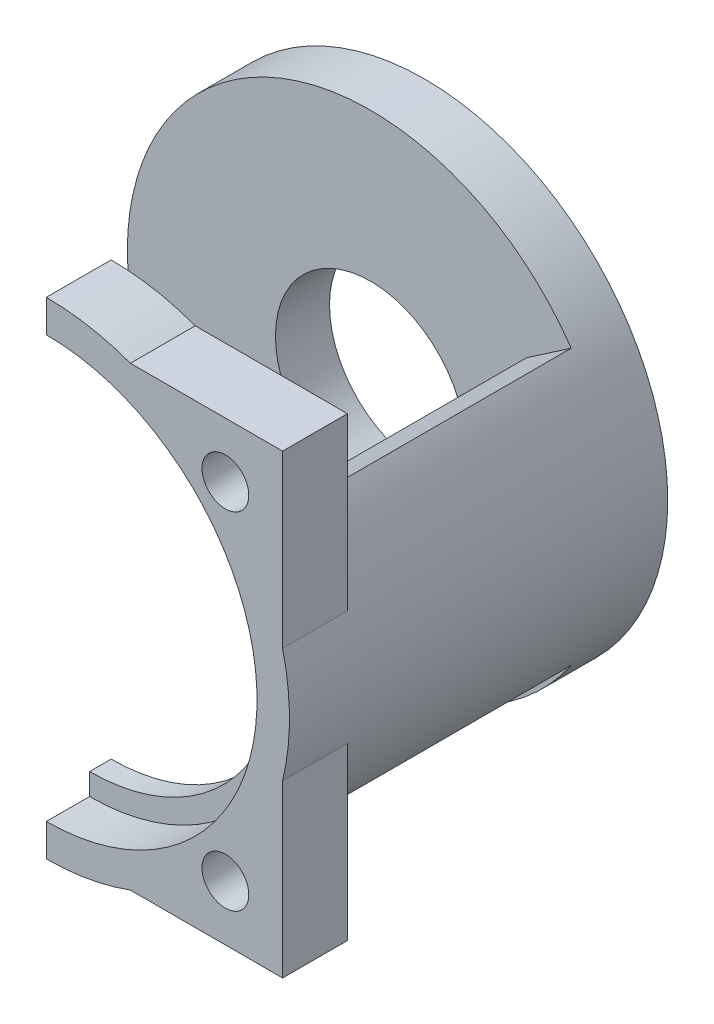
SolidWorks part; units mm, degrees
ref_plane "Front Plane" through (0, 0, 0) normal (0, 0, 1) x (1, 0, 0)
ref_plane "Top Plane" through (0, 0, 0) normal (0, 1, 0) x (1, 0, 0)
ref_plane "Right Plane" through (0, 0, 0) normal (1, 0, 0) x (0, 0, -1)
sketch "Sketch1" plane through (0, 0, 0) normal (0, 0, 1) x (1, 0, 0)
  circle A0 centre (0, 0) radius 17.4995
  circle A1 centre (0, 0) radius 22.4995
  dimension "D1" = 34.9991
  dimension "D2" = 5
extrude "Boss-Extrude1" add sketch "Sketch1" along normal blind 6
sketch "Sketch2" plane through (0, 0, 6) normal (0, 0, 1) x (1, 0, 0)
  circle A0 centre (0, 0) radius 19.4995
  circle A1 centre (0, 0) radius 17.4995
  dimension "D1" = 2
extrude "Cut-Extrude1" cut sketch "Sketch2" against normal blind 4
sketch "Sketch3" plane through (0, 0, 0) normal (0, 0, -1) x (-1, 0, 0)
  line L0 (-7.7836, 21.1103) -> (-21.8646, 21.1103)
  line L1 (21.8646, -21.1103) -> (7.7836, -21.1103)
  line L2 (21.8646, -21.1103) -> (21.8646, -5.3073)
  line L3 (21.8646, 21.1103) -> (7.7836, 21.1103)
  line L4 (-21.8646, -21.1103) -> (-21.8646, -5.3073)
  line L5 (21.8646, -21.1103) -> (-21.8646, 21.1103) construction
  line L6 (21.8646, 21.1103) -> (-21.8646, -21.1103) construction
  line L7 (16.5717, -16) -> (15.8186, -16) construction
  line L8 (16.5717, -16) -> (16.5717, 16) construction
  line L9 (16.5717, 16) -> (-16.5717, 16) construction
  line L10 (-16.5717, -16) -> (-16.5717, -15.2187) construction
  line L11 (16.5717, -16) -> (-16.5717, 16) construction
  line L12 (16.5717, 16) -> (-16.5717, -16) construction
  line L13 (21.8646, 5.3073) -> (21.8646, 21.1103)
  line L14 (-21.8646, 5.3073) -> (-21.8646, 21.1103)
  line L15 (-16.5717, 15.2187) -> (-16.5717, 16) construction
  line L16 (-15.8186, -16) -> (-16.5717, -16) construction
  line L17 (-7.7836, -21.1103) -> (-21.8646, -21.1103)
  arc A4 (-7.7836, 21.1103) -> (-21.8646, 5.3073) centre (0, 0) ccw
  arc A5 (21.8646, 5.3073) -> (7.7836, 21.1103) centre (0, 0) ccw
  arc A6 (-21.8646, -5.3073) -> (-7.7836, -21.1103) centre (0, 0) ccw
  arc A7 (7.7836, -21.1103) -> (21.8646, -5.3073) centre (0, 0) ccw
  circle A8 centre (0, 0) radius 22.4995 construction
  point P0 (0, 0)
  point P6 (0, 0)
  dimension "D1" = 42.2206
  dimension "D2" = 32
extrude "Boss-Extrude2" add sketch "Sketch3" against normal through all
sketch "Sketch5" plane through (0, 0, 0) normal (0, 0, -1) x (-1, 0, 0)
  line L0 (-14.4415, 9.8831) -> (-18.5678, 12.707)
  line L2 (-14.4415, -9.8831) -> (-18.5678, -12.707)
  line L4 (22.4995, 0) -> (0, 0) construction
  line L5 (-17.4995, 0) -> (-49.8767, 0) construction
  arc A0 (-18.5678, 12.707) -> (-18.5678, -12.707) centre (0, 0) ccw
  arc A1 (-14.4415, 9.8831) -> (-14.4415, -9.8831) centre (0, 0) ccw
extrude "Boss-Extrude3" add sketch "Sketch5" along normal blind 24
sketch "Sketch6" plane through (0, 0, -24) normal (0, 0, -1) x (-1, 0, 0)
  circle A0 centre (0, 0) radius 22.4995
  circle A1 centre (0, 0) radius 8.7945
  dimension "D1" = 17.5891
extrude "Boss-Extrude4" add sketch "Sketch6" along normal blind 5
sketch "Sketch7" plane through (0, 0, 0) normal (0, 0, -1) x (-1, 0, 0)
  line L0 (0, 20.425) -> (0, -31.8135)
  line L4 (0, 20.425) -> (0, 25.7891)
  line L5 (0, 25.7891) -> (-0.6602, 29.5853)
  line L6 (-0.6602, 29.5853) -> (38.0711, 28.4)
  line L7 (38.0711, 28.4) -> (36.3141, -29.0102)
  line L8 (36.3141, -29.0102) -> (0, -31.8135)
extrude "Cut-Extrude2" cut sketch "Sketch7" against normal through all
sketch "Sketch8" plane through (0, 0, 0) normal (-1, 0, 0) x (0, 0, 1)
  line L1 (10.3116, 30.4518) -> (36.6537, 30.4518)
  line L2 (10.3116, 30.4518) -> (10.3116, -32.3334)
  line L3 (10.3116, -32.3334) -> (36.6537, -32.3334)
  line L4 (36.6537, 30.4518) -> (36.6537, -32.3334)
sketch "Sketch9" plane through (0, 0, 0) normal (0, 0, -1) x (-1, 0, 0)
  circle A0 centre (16.5717, 16) radius 2.165
  circle A1 centre (16.5717, -16) radius 2.165
  circle A2 centre (-16.5717, -16) radius 2.165
  circle A3 centre (-16.5717, 16) radius 2.165
  dimension "D1" = 4.33
extrude "Cut-Extrude4" cut sketch "Sketch9" against normal through all
